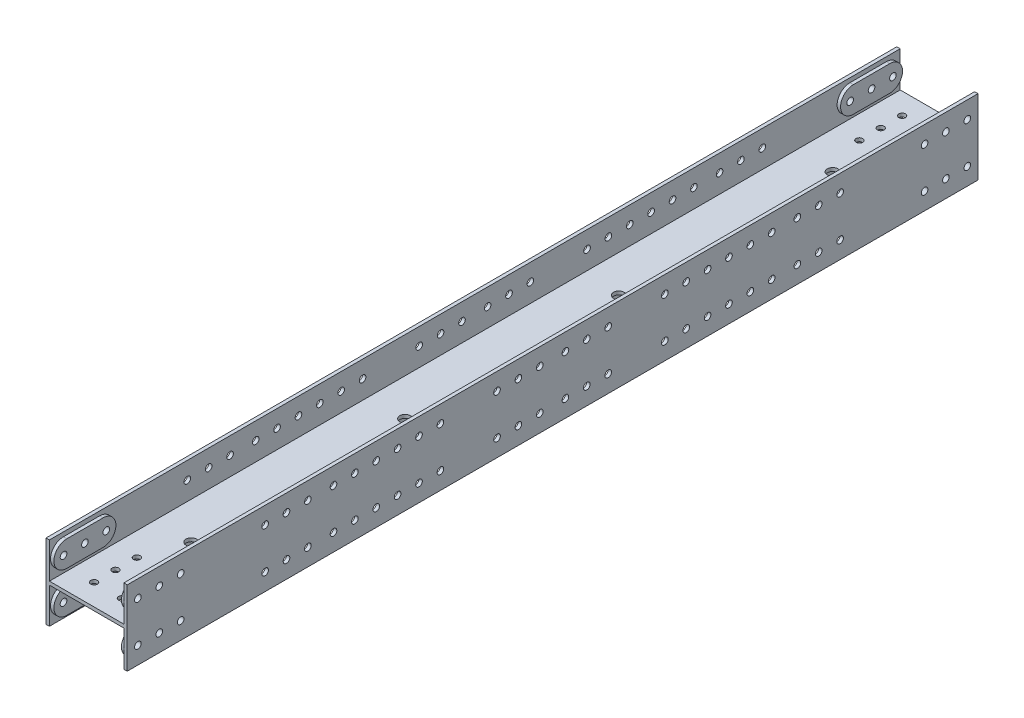
SolidWorks part; units mm, degrees
ref_plane "前视基准面" through (0, 0, 0) normal (0, 0, 1) x (1, 0, 0)
ref_plane "上视基准面" through (0, 0, 0) normal (0, 1, 0) x (1, 0, 0)
ref_plane "右视基准面" through (0, 0, 0) normal (1, 0, 0) x (0, 0, -1)
sketch "草图3" plane through (0, 0, 0) normal (0, 0, 1) x (1, 0, 0)
  line L1 (-187.8518, 0) -> (209.8413, 0) construction
  line L3 (0, 257.517) -> (0, -232.3948) construction
  line L4 (174, -8) -> (-174, -8)
  line L5 (174, 8) -> (174, 175)
  line L6 (-174, 175) -> (-190, 175)
  line L7 (-190, 175) -> (-190, -175)
  line L8 (-190, -175) -> (-174, -175)
  line L9 (-174, -175) -> (-174, -8)
  line L10 (-174, 8) -> (174, 8)
  line L11 (-174, 8) -> (-174, 175)
  line L12 (174, -175) -> (174, -8)
  line L13 (190, -175) -> (174, -175)
  line L14 (190, 175) -> (190, -175)
  line L15 (174, 175) -> (190, 175)
  point P15 (0, -8)
  point P16 (0, 8)
  dimension "D1" = 350
  dimension "D2" = 16
  dimension "D3" = 16
  dimension "D4" = 380
  dimension "D5" = 16
extrude "拉伸1" add sketch "草图3" along normal mid plane 3980
sketch "草图6" plane through (0, 0, 0) normal (0, 1, 0) x (1, 0, 0)
  line L0 (174, 0) -> (-49826, 0) construction
  line L1 (0, 602.5985) -> (0, -4597.2067) construction
  line L2 (174, -1990) -> (-174, -1990) construction
  line L3 (-190, -1990) -> (-190, 1990) construction
  line L4 (174, -1990) -> (174, 1990) construction
  line L5 (-174, -1990) -> (-174, 1990) construction
  circle A0 centre (-65, -1890) radius 15.5
  circle A1 centre (-65, -1790) radius 15.5
  circle A2 centre (-65, -1690) radius 15.5
  circle A3 centre (65, -1890) radius 15.5
  circle A4 centre (65, -1790) radius 15.5
  circle A5 centre (65, -1690) radius 15.5
  circle A6 centre (0, -1500) radius 25
  circle A7 centre (0, -500) radius 25
  circle A8 centre (0, 500) radius 25
  circle A9 centre (0, 1500) radius 25
  circle A10 centre (65, 1690) radius 15.5
  circle A11 centre (65, 1790) radius 15.5
  circle A12 centre (65, 1890) radius 15.5
  circle A13 centre (-65, 1690) radius 15.5
  circle A14 centre (-65, 1790) radius 15.5
  circle A15 centre (-65, 1890) radius 15.5
  point P41 (174, 0)
  point P44 (-174, 0)
  dimension "D1" = 31
  dimension "D7" = 50
  dimension "D9" = 50
  dimension "D2" = 100
  dimension "D3" = 100
  dimension "D4" = 100
  dimension "D5" = 125
  dimension "D6" = 65
  dimension "D8" = 190
  dimension "D10" = 1000
extrude "拉伸2" cut sketch "草图6" against normal through all and the other way through all
sketch "草图9" plane through (174, 0, 0) normal (-1, 0, 0) x (0, 0, 1)
  line L0 (-1755, -95) -> (-1925, -95) construction
  line L2 (-1755, -155) -> (-1925, -155)
  line L3 (0, 0) -> (-35.9854, 0) construction
  line L4 (-35.9854, 0) -> (4015.6483, 0) construction
  line L5 (0, 175) -> (0, -49825) construction
  line L6 (1990, 175) -> (-1990, 175) construction
  line L7 (1990, -175) -> (-1990, -175) construction
  line L8 (-1755, -35) -> (-1925, -35)
  line L9 (1755, -95) -> (1925, -95) construction
  line L10 (1755, -155) -> (1925, -155)
  line L11 (1755, -35) -> (1925, -35)
  line L12 (1755, 95) -> (1925, 95) construction
  line L13 (1755, 155) -> (1925, 155)
  line L14 (-1755, 95) -> (-1925, 95) construction
  line L15 (-1755, 155) -> (-1925, 155)
  line L16 (-1755, 35) -> (-1925, 35)
  line L17 (-1990, 175) -> (-1990, -175) construction
  line L18 (1755, 35) -> (1925, 35)
  arc A0 (-1755, -155) -> (-1755, -35) centre (-1755, -95) ccw
  arc A1 (-1925, -35) -> (-1925, -155) centre (-1925, -95) ccw
  arc A2 (1755, -155) -> (1755, -35) centre (1755, -95) cw
  arc A3 (1925, -35) -> (1925, -155) centre (1925, -95) cw
  arc A4 (1755, 155) -> (1755, 35) centre (1755, 95) ccw
  arc A5 (1925, 35) -> (1925, 155) centre (1925, 95) ccw
  arc A8 (-1755, 155) -> (-1755, 35) centre (-1755, 95) cw
  arc A9 (-1925, 35) -> (-1925, 155) centre (-1925, 95) cw
  point P6 (0, 175)
  point P9 (-1840, -95)
  point P18 (0, -175)
  point P24 (1840, -95)
  point P31 (1840, 95)
  point P37 (-1840, 95)
  dimension "D1" = 65
  dimension "D2" = 170
  dimension "D3" = 80
  dimension "D4" = 60
extrude "拉伸4" add sketch "草图9" along normal blind 16
mirror "镜向1" about plane through (0, 0, 0) normal (1, 0, 0) of "拉伸4"
sketch "草图4" plane through (0, 0, 0) normal (1, 0, 0) x (0, 0, -1)
  line L0 (-1990, 175) -> (1990, 175) construction
  line L1 (0, 175) -> (0, -49825) construction
  line L2 (91.7311, 0) -> (-4448.0759, 0) construction
  line L3 (-1990, -175) -> (1990, -175) construction
  line L6 (-1990, -175) -> (-1990, 175) construction
  circle A0 centre (-1940, 95) radius 15.5
  circle A1 centre (-1840, 95) radius 15.5
  circle A2 centre (-1740, 95) radius 15.5
  circle A3 centre (-1345, 95) radius 15.5
  circle A4 centre (-1245, 95) radius 15.5
  circle A5 centre (-1145, 95) radius 15.5
  circle A6 centre (-260, 95) radius 15.5
  circle A7 centre (-160, 95) radius 15.5
  circle A8 centre (-60, 95) radius 15.5
  circle A9 centre (-525, -95) radius 15.5
  circle A10 centre (-625, -95) radius 15.5
  circle A11 centre (-725, -95) radius 15.5
  circle A12 centre (-825, -95) radius 15.5
  circle A13 centre (-925, -95) radius 15.5
  circle A14 centre (-1025, -95) radius 15.5
  circle A15 centre (-60, -95) radius 15.5
  circle A16 centre (-160, -95) radius 15.5
  circle A17 centre (-260, -95) radius 15.5
  circle A18 centre (-1145, -95) radius 15.5
  circle A19 centre (-1245, -95) radius 15.5
  circle A20 centre (-1345, -95) radius 15.5
  circle A21 centre (-1740, -95) radius 15.5
  circle A22 centre (-1840, -95) radius 15.5
  circle A23 centre (-1940, -95) radius 15.5
  circle A24 centre (-1025, 95) radius 15.5
  circle A25 centre (-925, 95) radius 15.5
  circle A26 centre (-825, 95) radius 15.5
  circle A27 centre (-725, 95) radius 15.5
  circle A28 centre (-625, 95) radius 15.5
  circle A29 centre (-525, 95) radius 15.5
  circle A30 centre (525, 95) radius 15.5
  circle A31 centre (625, 95) radius 15.5
  circle A32 centre (725, 95) radius 15.5
  circle A33 centre (825, 95) radius 15.5
  circle A34 centre (925, 95) radius 15.5
  circle A35 centre (1025, 95) radius 15.5
  circle A36 centre (1940, -95) radius 15.5
  circle A37 centre (1840, -95) radius 15.5
  circle A38 centre (1740, -95) radius 15.5
  circle A39 centre (1345, -95) radius 15.5
  circle A40 centre (1245, -95) radius 15.5
  circle A41 centre (1145, -95) radius 15.5
  circle A42 centre (260, -95) radius 15.5
  circle A43 centre (160, -95) radius 15.5
  circle A44 centre (60, -95) radius 15.5
  circle A45 centre (1025, -95) radius 15.5
  circle A46 centre (925, -95) radius 15.5
  circle A47 centre (825, -95) radius 15.5
  circle A48 centre (725, -95) radius 15.5
  circle A49 centre (625, -95) radius 15.5
  circle A50 centre (525, -95) radius 15.5
  circle A51 centre (60, 95) radius 15.5
  circle A52 centre (160, 95) radius 15.5
  circle A53 centre (260, 95) radius 15.5
  circle A54 centre (1145, 95) radius 15.5
  circle A55 centre (1245, 95) radius 15.5
  circle A56 centre (1345, 95) radius 15.5
  circle A57 centre (1740, 95) radius 15.5
  circle A58 centre (1840, 95) radius 15.5
  circle A59 centre (1940, 95) radius 15.5
  point P12 (0, 175)
  point P23 (0, -175)
  dimension "D6" = 31
  dimension "D7" = 395
  dimension "D8" = 31
  dimension "D1" = 80
  dimension "D2" = 95
  dimension "D3" = 50
  dimension "D4" = 100
  dimension "D5" = 100
  dimension "D9" = 100
  dimension "D10" = 100
  dimension "D11" = 265
  dimension "D12" = 120
  dimension "D13" = 100
  dimension "D14" = 100
  dimension "D15" = 60
extrude "拉伸6" cut sketch "草图4" against normal through all and the other way through all
